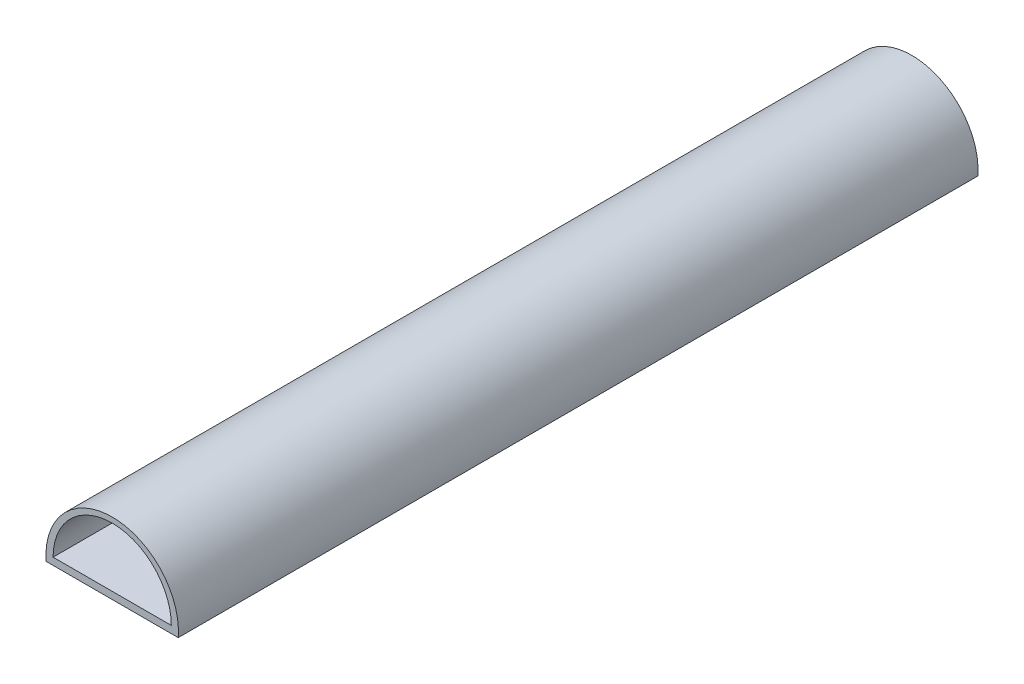
SolidWorks part; units mm, degrees
material "PVC 0.007 Plasticized"
ref_plane "Front Plane" through (0, 0, 0) normal (0, 0, 1) x (1, 0, 0)
ref_plane "Top Plane" through (0, 0, 0) normal (0, 1, 0) x (1, 0, 0)
ref_plane "Right Plane" through (0, 0, 0) normal (1, 0, 0) x (0, 0, -1)
sketch "Sketch1" plane through (0, 0, 0) normal (0, 0, 1) x (1, 0, 0)
  line L0 (-23.1114, -10.0484) -> (6.2574, -10.0484)
  line L2 (-8.427, -8.4609) -> (-21.5715, -8.4609)
  line L3 (-8.427, -8.4609) -> (4.7175, -8.4609)
  arc A0 (-23.1114, -10.0484) -> (6.2574, -10.0484) centre (-8.427, -8.8769) cw
  arc A1 (-21.5715, -8.4609) -> (4.7175, -8.4609) centre (-8.427, -8.4609) cw
extrude "Boss-Extrude2" add sketch "Sketch1" along normal blind 177.8
